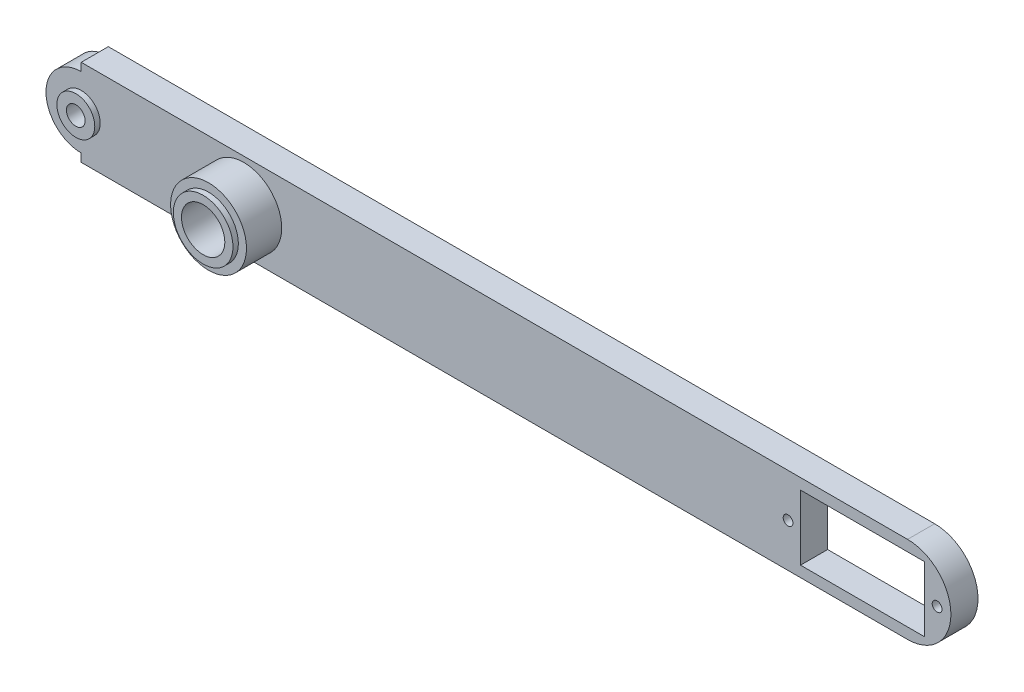
SolidWorks part; units mm, degrees
ref_plane "Front Plane" through (0, 0, 0) normal (0, 0, 1) x (1, 0, 0)
ref_plane "Top Plane" through (0, 0, 0) normal (0, 1, 0) x (1, 0, 0)
ref_plane "Right Plane" through (0, 0, 0) normal (1, 0, 0) x (0, 0, -1)
sketch "Sketch1" plane through (0, 0, 0) normal (0, 0, 1) x (1, 0, 0)
  line L0 (-30, -8) -> (122.5, -8)
  line L1 (122.5, -8) -> (122.5, 8)
  line L2 (122.5, 8) -> (-30, 8)
  line L3 (-30, 8) -> (-30, -8)
extrude "Boss-Extrude1" add sketch "Sketch1" along normal blind 5 from offset 9
sketch "Sketch2" plane through (0, 0, 0) normal (0, 0, 1) x (1, 0, 0)
  circle A0 centre (-30, 0) radius 6.5
extrude "Boss-Extrude2" add sketch "Sketch2" along normal blind 5 from offset 9
sketch "Sketch3" plane through (0, 0, 0) normal (0, 0, 1) x (1, 0, 0)
  circle A0 centre (122.5, 0) radius 8
extrude "Boss-Extrude3" add sketch "Sketch3" along normal blind 5 from offset 9
sketch "Sketch4" plane through (0, 0, 0) normal (0, 0, 1) x (1, 0, 0)
  circle A0 centre (0, 0) radius 7
extrude "Boss-Extrude4" add sketch "Sketch4" along normal blind 11.5 from offset 9
sketch "Sketch5" plane through (0, 0, 0) normal (0, 0, 1) x (1, 0, 0)
  circle A0 centre (0, 0) radius 5.5
extrude "Boss-Extrude5" add sketch "Sketch5" along normal blind 1 from offset 2.5
sketch "Sketch6" plane through (0, 0, 0) normal (0, 0, 1) x (1, 0, 0)
  circle A0 centre (-30, 0) radius 3.5
extrude "Boss-Extrude6" add sketch "Sketch6" along normal blind 1 from offset 4
sketch "Sketch7" plane through (0, 0, 0) normal (0, 0, 1) x (1, 0, 0)
  circle A0 centre (0, 0) radius 4
extrude "Cut-Extrude1" cut sketch "Sketch7" against normal through all and the other way through all
sketch "Sketch8" plane through (0, 0, 0) normal (0, 0, 1) x (1, 0, 0)
  circle A0 centre (-30, 0) radius 1.725
extrude "Cut-Extrude2" cut sketch "Sketch8" against normal through all and the other way through all
sketch "Sketch9" plane through (0, 0, 0) normal (0, 0, 1) x (1, 0, 0)
  line L0 (102.75, -6) -> (125.65, -6)
  line L1 (125.65, -6) -> (125.65, 6)
  line L2 (125.65, 6) -> (102.75, 6)
  line L3 (102.75, 6) -> (102.75, -6)
extrude "Cut-Extrude3" cut sketch "Sketch9" against normal through all and the other way through all
sketch "Sketch10" plane through (0, 0, 0) normal (0, 0, 1) x (1, 0, 0)
  circle A0 centre (100.45, 0) radius 0.9
  circle A1 centre (127.95, 0) radius 0.9
extrude "Cut-Extrude4" cut sketch "Sketch10" against normal through all and the other way through all
sketch "Sketch11" plane through (0, 0, 0) normal (0, 0, 1) x (1, 0, 0)
  circle A0 centre (40, 0) radius 2
  circle A1 centre (75, 0) radius 2
extrude "Cut-Extrude5" cut sketch "Sketch11" along normal blind 4 from offset 9
